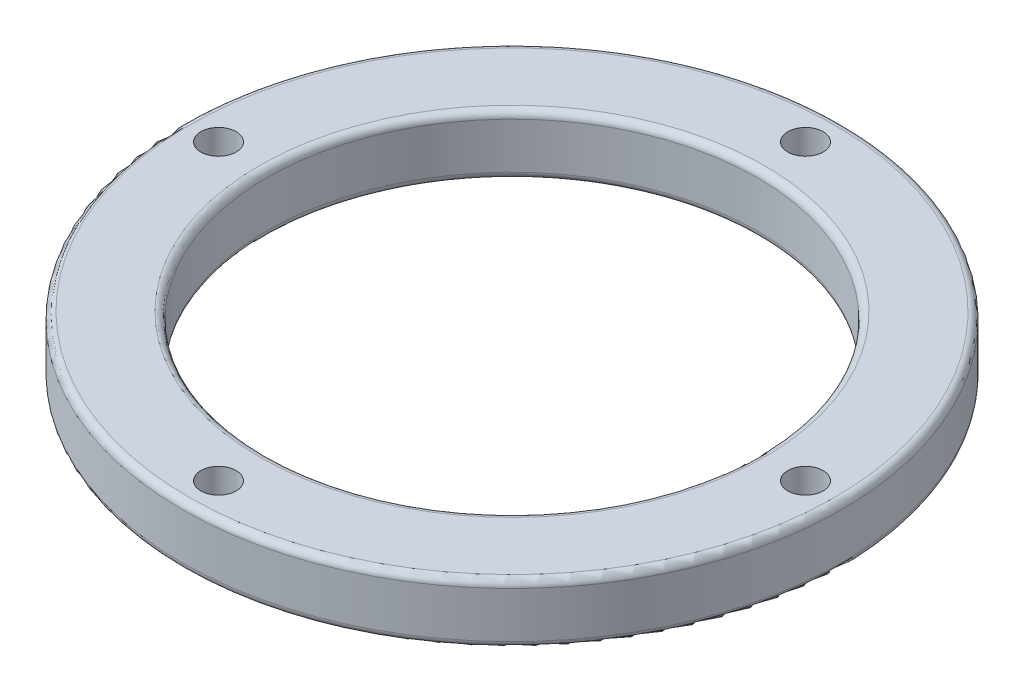
SolidWorks part; units mm, degrees
ref_plane "Front Plane" through (0, 0, 0) normal (0, 0, 1) x (1, 0, 0)
ref_plane "Top Plane" through (0, 0, 0) normal (0, 1, 0) x (1, 0, 0)
ref_plane "Right Plane" through (0, 0, 0) normal (1, 0, 0) x (0, 0, -1)
sketch "Sketch1" plane through (0, 0, 0) normal (0, 1, 0) x (1, 0, 0)
  line L0 (0, 0) -> (0, 46.6) construction
  circle A0 centre (0, 0) radius 34.7
  circle A1 centre (0, 0) radius 46.6
  circle A2 centre (0, 41.5) radius 2.5
  circle A3 centre (41.5, 0) radius 2.5
  circle A4 centre (0, -41.5) radius 2.5
  circle A5 centre (-41.5, 0) radius 2.5
  point P16 (0, 0)
  dimension "D1" = 69.4
  dimension "D2" = 93.2
  dimension "D4" = 5
  dimension "D3" = 41.5
  dimension "D5" = 4
extrude "Boss-Extrude1" add sketch "Sketch1" along normal blind 8.5
fillet "Fillet1" radius 1 4 edges at (0, 0, 46.6) (0, 8.5, 46.6) (0, 0, 34.7) (0, 8.5, 34.7)
